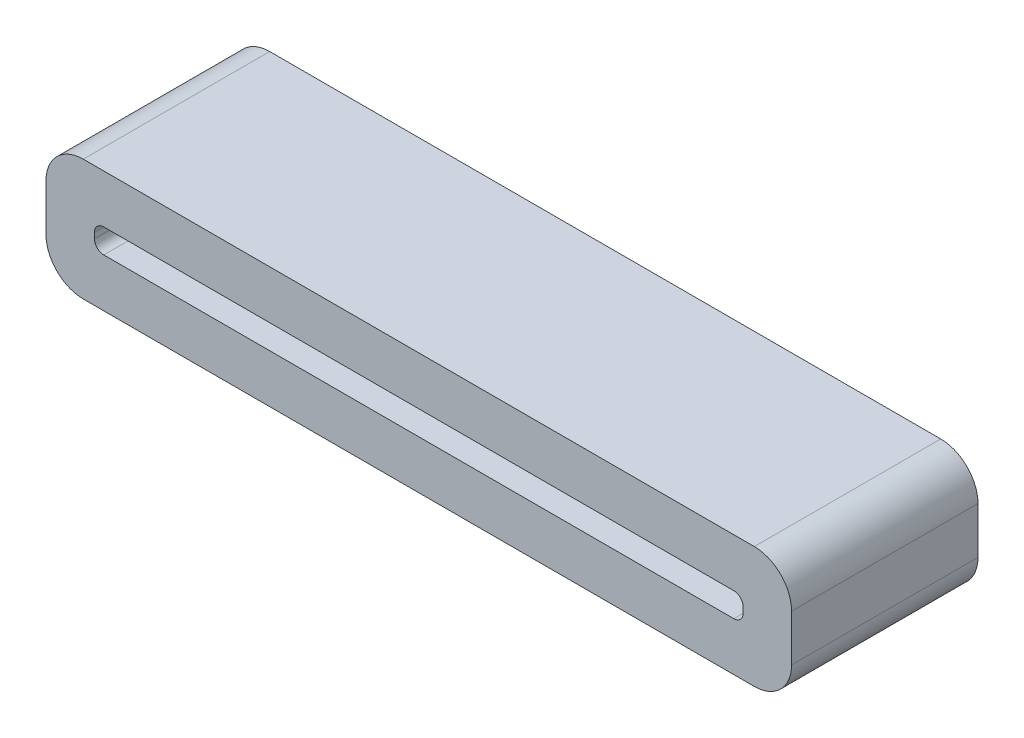
SolidWorks part; units mm, degrees
ref_plane "Face" through (0, 0, 0) normal (0, 0, 1) x (1, 0, 0)
ref_plane "Dessus" through (0, 0, 0) normal (0, 1, 0) x (1, 0, 0)
ref_plane "Droite" through (0, 0, 0) normal (1, 0, 0) x (0, 0, -1)
sketch "Esquisse1" plane through (0, 0, 0) normal (0, 0, 1) x (1, 0, 0)
  line L0 (-29.5866, 9.6951) -> (6.4134, 9.6951)
  line L1 (-28.4866, 7.0951) -> (5.3134, 7.0951)
  line L2 (-28.9866, 6.5951) -> (-28.9866, 6.2951)
  line L3 (-28.4866, 5.7951) -> (5.3134, 5.7951)
  line L4 (5.8134, 6.5951) -> (5.8134, 6.2951)
  line L5 (8.4134, 7.6951) -> (8.4134, 5.1951)
  line L6 (-29.5866, 3.1951) -> (6.4134, 3.1951)
  line L7 (-31.5866, 7.6951) -> (-31.5866, 5.1951)
  line L8 (-28.9866, 7.0951) -> (-28.9866, 5.7951) construction
  line L9 (-28.9866, 7.0951) -> (5.8134, 7.0951) construction
  line L10 (-28.9866, 5.7951) -> (5.8134, 5.7951) construction
  line L11 (5.8134, 7.0951) -> (5.8134, 5.7951) construction
  line L12 (8.4134, 9.6951) -> (8.4134, 3.1951) construction
  line L13 (-31.5866, 9.6951) -> (8.4134, 9.6951) construction
  line L14 (-31.5866, 3.1951) -> (8.4134, 3.1951) construction
  line L15 (-31.5866, 9.6951) -> (-31.5866, 3.1951) construction
  arc A0 (-28.9866, 6.5951) -> (-28.4866, 7.0951) centre (-28.4866, 6.5951) cw
  arc A1 (-28.9866, 6.2951) -> (-28.4866, 5.7951) centre (-28.4866, 6.2951) ccw
  arc A2 (5.8134, 6.5951) -> (5.3134, 7.0951) centre (5.3134, 6.5951) ccw
  arc A3 (5.3134, 5.7951) -> (5.8134, 6.2951) centre (5.3134, 6.2951) ccw
  arc A4 (8.4134, 7.6951) -> (6.4134, 9.6951) centre (6.4134, 7.6951) ccw
  arc A5 (6.4134, 3.1951) -> (8.4134, 5.1951) centre (6.4134, 5.1951) ccw
  arc A6 (-31.5866, 7.6951) -> (-29.5866, 9.6951) centre (-29.5866, 7.6951) cw
  arc A7 (-29.5866, 3.1951) -> (-31.5866, 5.1951) centre (-29.5866, 5.1951) cw
  dimension "D4" = 0.5
  dimension "D5" = 2
  dimension "D6" = 2
  dimension "D2" = 1.3
  dimension "D3" = 34.8
  dimension "D1" = 2.6
extrude "Extrusion1" add sketch "Esquisse1" against normal blind 10
